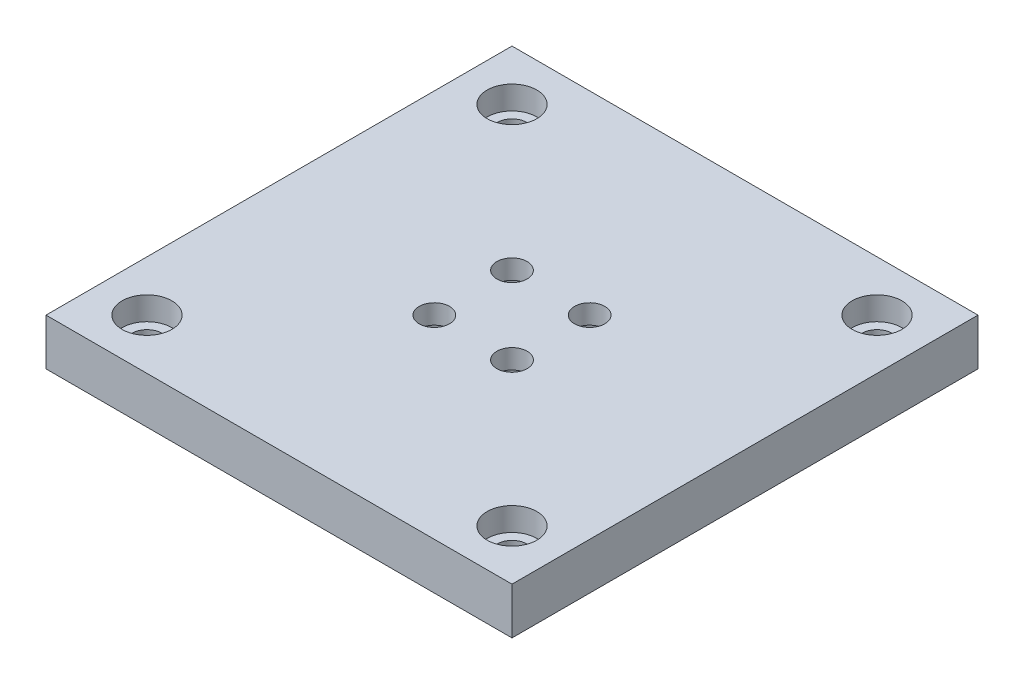
SolidWorks part; units mm, degrees
ref_plane "Ebene vorne" through (0, 0, 0) normal (0, 0, 1) x (1, 0, 0)
ref_plane "Ebene oben" through (0, 0, 0) normal (0, 1, 0) x (1, 0, 0)
ref_plane "Ebene rechts" through (0, 0, 0) normal (1, 0, 0) x (0, 0, -1)
sketch "Skizze1" plane through (0, 0, 0) normal (0, 1, 0) x (1, 0, 0)
  line L1 (0, 0) -> (50, 0) construction
  line L2 (0, 0) -> (0, 60) construction
  line L3 (0, 60) -> (50, 60) construction
  line L4 (50, 0) -> (50, 60) construction
  line L5 (10, 55) -> (40, 55) construction
  line L6 (10, 55) -> (10, 5) construction
  line L7 (10, 5) -> (40, 5) construction
  line L8 (40, 55) -> (40, 5) construction
  line L9 (-5, 0) -> (55, 0)
  line L10 (-5, 0) -> (-5, 60)
  line L11 (-5, 60) -> (55, 60)
  line L12 (55, 0) -> (55, 60)
  point P9 (10, 30)
  point P10 (0, 30)
  point P11 (25, 55)
  point P12 (25, 60)
  point P13 (25, 30)
  point P19 (55, 30)
  point P20 (25, 60)
  dimension "D5" = 60
  dimension "D1" = 50
  dimension "D2" = 60
  dimension "D3" = 10
  dimension "D4" = 5
extrude "Aufsatz-Linear austragen1" add sketch "Skizze1" along normal blind 6
sketch "Skizze2" plane through (0, 0, 0) normal (0, -1, 0) x (1, 0, 0)
  line L0 (55, 0) -> (55, -60) construction
  line L1 (55, -60) -> (-5, -60) construction
  point P0 (20, -25)
  point P1 (30, -25)
  point P2 (30, -35)
  point P3 (25, -30)
  point P4 (20, -35)
  point P10 (25, -30)
  dimension "D1" = 5
  dimension "D2" = 5
  dimension "D3" = 10
  dimension "D4" = 5
  dimension "D5" = 30
  dimension "D6" = 30
hole_wizard "Bohrung3" positions "3D-Skizze4" profile "Skizze6" legacy end condition through all
sketch3d "3D-Skizze4"
  point P0 (20, 0, -25)
  point P3 (30, 0, -25)
  point P6 (30, 0, -35)
  point P9 (20, 0, -35)
sketch "Skizze6" plane through (20, 0, -25) normal (1, 0, 0) x (0, 0, -1)
  line L0 (0, 0) -> (0, 6)
  line L1 (0, 6) -> (1.95, 6)
  line L2 (1.95, 6) -> (1.95, 3.5)
  line L3 (1.95, 3.5) -> (3.2, 3.5)
  line L4 (3.2, 3.5) -> (3.2, 0)
  line L5 (3.2, 0) -> (0, 0)
  line L6 (0, 110) -> (0, -10) construction
  dimension "Durchmesser" = 3.9
  dimension "Tiefe" = 6
  dimension "Senkdurchmesser1" = 6.4
  dimension "Senktiefe1" = 3.5
sketch "Skizze7" plane through (0, 6, 0) normal (0, 1, 0) x (1, 0, 0)
  line L1 (5, 10) -> (45, 10) construction
  line L2 (5, 10) -> (5, 50) construction
  line L3 (5, 50) -> (45, 50) construction
  line L4 (45, 10) -> (45, 50) construction
  line L5 (5, 10) -> (45, 50) construction
  line L6 (5, 50) -> (45, 10) construction
  line L7 (1.5, 53.5) -> (1.5, 6.5) construction
  line L8 (48.5, 53.5) -> (48.5, 6.5) construction
  line L10 (48.5, 6.5) -> (1.5, 6.5) construction
  line L11 (1.5, 53.5) -> (48.5, 53.5) construction
  point P0 (25, 30)
  point P5 (25, 53.5)
  point P10 (48.5, 30)
  dimension "D1" = 47
  dimension "D2" = 40
  dimension "D3" = 47
hole_wizard "Bohrung4" positions "3D-Skizze5" profile "Skizze8" legacy
sketch3d "3D-Skizze5"
  point P0 (1.5, 6, -53.5)
  point P3 (48.5, 6, -53.5)
  point P6 (48.5, 6, -6.5)
  point P9 (1.5, 6, -6.5)
sketch "Skizze8" plane through (1.5, 6, -53.5) normal (1, 0, 0) x (0, 0, 1)
  line L0 (0, 0) -> (0, 100)
  line L1 (0, 100) -> (1.95, 100)
  line L2 (1.95, 100) -> (1.95, 3)
  line L3 (1.95, 3) -> (3.2, 3)
  line L4 (3.2, 3) -> (3.2, 0)
  line L5 (3.2, 0) -> (0, 0)
  line L6 (0, 110) -> (0, -10) construction
  dimension "Durchmesser" = 3.9
  dimension "Tiefe" = 100
  dimension "Senkdurchmesser1" = 6.4
  dimension "Senktiefe1" = 3
